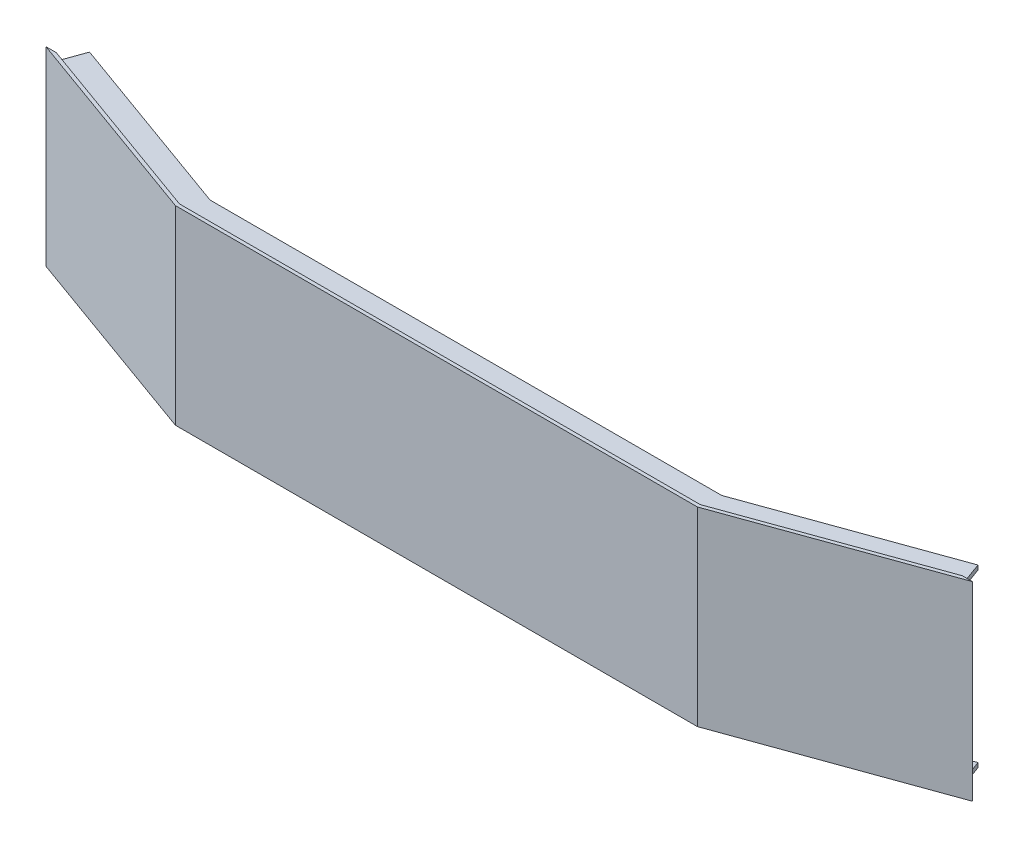
SolidWorks part; units mm, degrees
ref_plane "Front Plane" through (0, 0, 0) normal (0, 0, 1) x (1, 0, 0)
ref_plane "Top Plane" through (0, 0, 0) normal (0, 1, 0) x (1, 0, 0)
ref_plane "Right Plane" through (0, 0, 0) normal (1, 0, 0) x (0, 0, -1)
sketch "Sketch1" plane through (0, 0, 0) normal (0, 1, 0) x (1, 0, 0)
  line L0 (-261, -120) -> (-150, -160)
  line L1 (-150, -160) -> (150, -160)
  line L2 (150, -160) -> (261, -120)
  line L3 (261, -120) -> (-261, -120) construction
  line L5 (-150.3494, -162) -> (150.3494, -162)
  line L8 (-257.4765, -120) -> (-261, -120)
  line L9 (-261, -120) -> (-266.8994, -120)
  line L10 (261, -120) -> (266.8994, -120)
  line L11 (-272.4494, -118) -> (-150.3494, -162) construction
  line L12 (266.8994, -120) -> (150.3494, -162)
  line L13 (150.3494, -162) -> (272.4494, -118) construction
  line L14 (272.4494, -118) -> (-272.4494, -118) construction
  line L15 (-150.3494, -162) -> (-266.8994, -120)
  dimension "D1" = 2
extrude "Boss-Extrude1" add sketch "Sketch1" along normal blind 109.6 contours L0 L1 L2 L10 L12 L5 L15 L9
ref_plane "Plane1" through (0, 4.25, 0) normal (0, 1, 0) x (1, 0, 0)
ref_plane "Plane2" through (0, 105.35, 0) normal (0, 1, 0) x (1, 0, 0)
sketch "Sketch2" plane through (0, 4.25, 0) normal (0, 1, 0) x (1, 0, 0)
  line L9 (147.3798, -145) -> (255.9147, -105.8883)
  line L10 (-147.3798, -145) -> (147.3798, -145)
  line L11 (-255.9147, -105.8883) -> (-147.3798, -145)
  line L12 (147.3798, -145) -> (255.9147, -105.8883)
  line L13 (-147.3798, -145) -> (147.3798, -145)
  line L14 (-255.9147, -105.8883) -> (-147.3798, -145)
  line L18 (-255.9147, -105.8883) -> (-261, -120)
  line L19 (255.9147, -105.8883) -> (261, -120)
  line L21 (150, -160) -> (261, -120)
  line L22 (-150, -160) -> (150, -160)
  line L23 (-261, -120) -> (-150, -160)
  line L24 (150, -160) -> (261, -120)
  line L25 (-150, -160) -> (150, -160)
  line L26 (-261, -120) -> (-150, -160)
  dimension "D1" = 15
  dimension "D2" = 0
sketch "Sketch4" plane through (0, 105.35, 0) normal (0, 1, 0) x (1, 0, 0)
  line L3 (-255.9147, -105.8883) -> (-147.3798, -145)
  line L4 (-147.3798, -145) -> (147.3798, -145)
  line L5 (147.3798, -145) -> (255.9147, -105.8883)
  line L9 (150, -160) -> (261, -120)
  line L10 (-150, -160) -> (150, -160)
  line L11 (-261, -120) -> (-150, -160)
  line L12 (150, -160) -> (261, -120)
  line L13 (-150, -160) -> (150, -160)
  line L14 (-261, -120) -> (-150, -160)
  line L19 (-261, -120) -> (-255.9147, -105.8883)
  line L22 (255.9147, -105.8883) -> (261, -120)
  dimension "D1" = 0
  dimension "D2" = 15
extrude "Boss-Extrude2" add sketch "Sketch2" along normal blind 2.54
extrude "Boss-Extrude3" add sketch "Sketch4" against normal blind 2.54
ref_plane "Plane3" through (-118.4369, 0, -20.6888) normal (0.9851, 0, 0.1721) x (0.1721, 0, -0.9851)
sketch "Sketch5" plane through (-118.4369, 0, -20.6888) normal (0.9851, 0, 0.1721) x (0.1721, 0, -0.9851)
  line L0 (-168.1977, 102.81) -> (-183.4249, 54.8)
  line L1 (-183.4249, 102.81) -> (-183.4249, 6.79) construction
  line L2 (-183.4249, 54.8) -> (-168.1977, 6.79) construction
rib "Rib2" sketch "Sketch5" sketch "Sketch5" thickness 2.54 extrusion direction parallel to sketch draft on no parameters "D1"=2.54
sketch "Sketch6" plane through (-118.4369, 0, -20.6888) normal (0.9851, 0, 0.1721) x (0.1721, 0, -0.9851)
  line L0 (-183.4249, 54.8) -> (-168.1977, 6.79)
rib "Rib3" sketch "Sketch6" sketch "Sketch6" thickness 2.54 extrusion direction parallel to sketch draft on no parameters "D1"=2.54
ref_plane "Plane4" through (118.4369, 0, -20.6888) normal (0.9851, 0, -0.1721) x (-0.1721, 0, -0.9851)
sketch "Sketch7" plane through (118.4369, 0, -20.6888) normal (0.9851, 0, -0.1721) x (-0.1721, 0, -0.9851)
  line L0 (-168.1977, 102.81) -> (-183.4249, 54.8)
  line L1 (-183.4249, 102.81) -> (-183.4249, 6.79) construction
  line L2 (-183.4249, 54.8) -> (-168.1977, 6.79) construction
rib "Rib4" sketch "Sketch7" sketch "Sketch7" thickness 2.54 extrusion direction parallel to sketch draft on no parameters "D1"=2.54
sketch "Sketch8" plane through (118.4369, 0, -20.6888) normal (0.9851, 0, -0.1721) x (-0.1721, 0, -0.9851)
  line L0 (-183.4249, 54.8) -> (-168.1977, 6.79)
rib "Rib5" sketch "Sketch8" sketch "Sketch8" thickness 2.54 extrusion direction parallel to sketch draft on no parameters "D1"=2.54
sketch "Sketch10" plane through (0, 0, 145) normal (0, 0, -1) x (-1, 0, 0)
  line L0 (0, 102.81) -> (0, 105.35) construction
  line L1 (-147.3798, 102.81) -> (147.3798, 102.81) construction
  line L2 (-147.3798, 105.35) -> (147.3798, 105.35) construction
  line L3 (0, 105.35) -> (0, 6.79) construction
  line L4 (-147.3798, 6.79) -> (147.3798, 6.79) construction
sketch "Sketch12" plane through (0, 0, 160) normal (0, 0, -1) x (-1, 0, 0)
  line L0 (0, 102.81) -> (0, 6.79) construction
sketch "Sketch13" plane through (0, 0, 0) normal (1, 0, 0) x (0, 0, -1)
  line L0 (-145, 102.81) -> (-160, 54.8)
  line L1 (-160, 102.81) -> (-160, 6.79) construction
  line L2 (-160, 54.8) -> (-145, 6.79) construction
rib "Rib6" sketch "Sketch13" sketch "Sketch13" thickness 2.54 extrusion direction parallel to sketch draft on no parameters "D1"=2.54
sketch "Sketch14" plane through (0, 0, 0) normal (1, 0, 0) x (0, 0, -1)
  line L0 (-160, 54.8) -> (-145, 6.79)
  line L1 (-160, 102.81) -> (-160, 6.79) construction
rib "Rib7" sketch "Sketch14" sketch "Sketch14" thickness 2.54 extrusion direction parallel to sketch draft on no parameters "D1"=2.54
equation "\"gap\"= 1mm"
equation "\"casewidth\"= 2.5mm"
